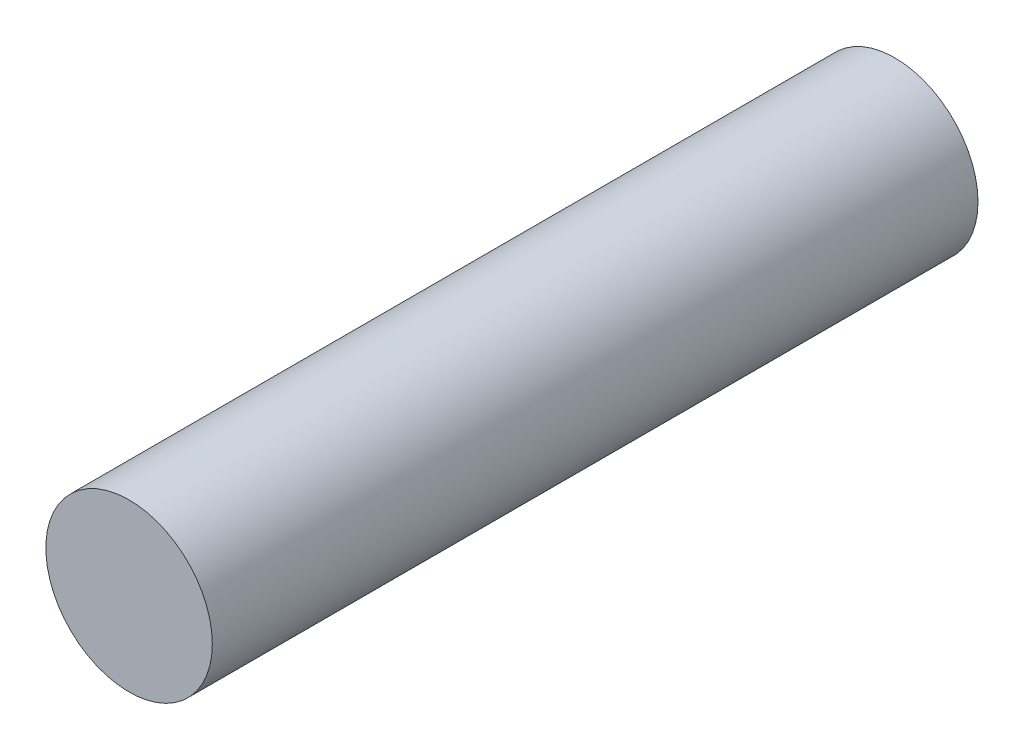
SolidWorks part; units mm, degrees
ref_plane "Plan de face" through (0, 0, 0) normal (0, 0, 1) x (1, 0, 0)
ref_plane "Plan de dessus" through (0, 0, 0) normal (0, 1, 0) x (1, 0, 0)
ref_plane "Plan de droite" through (0, 0, 0) normal (1, 0, 0) x (0, 0, -1)
sketch "Esquisse1" plane through (0, 0, 0) normal (0, 0, 1) x (1, 0, 0)
  circle A0 centre (0, 0) radius 2.5
  dimension "D1" = 5
extrude "Boss.-Extru.1" add sketch "Esquisse1" along normal blind 10
sketch "Esquisse2" plane through (0, 0, 10) normal (0, 0, 1) x (1, 0, 0)
  circle A0 centre (0, 0) radius 2.5
  dimension "D1" = 5
extrude "Boss.-Extru.2" add sketch "Esquisse2" along normal blind 13
